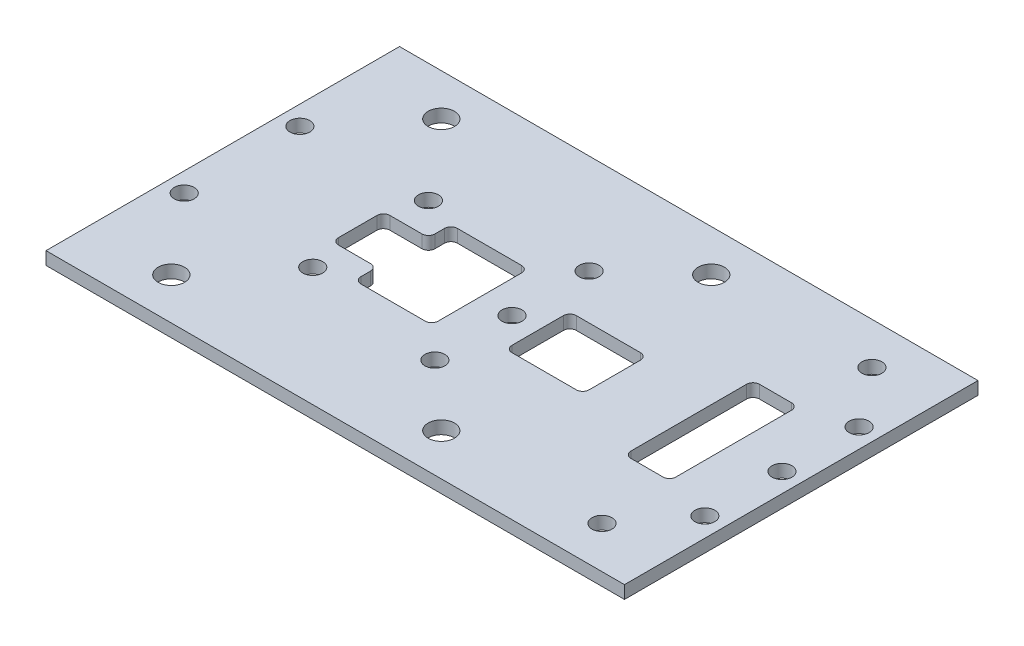
SolidWorks part; units mm, degrees
ref_plane "前视基准面" through (0, 0, 0) normal (0, 0, 1) x (1, 0, 0)
ref_plane "上视基准面" through (0, 0, 0) normal (0, 1, 0) x (1, 0, 0)
ref_plane "右视基准面" through (0, 0, 0) normal (1, 0, 0) x (0, 0, -1)
other "Configuration Table"
sketch "草图1" plane through (0, 0, 0) normal (0, 1, 0) x (1, 0, 0)
  line L1 (45, -27.5) -> (-45, -27.5)
  line L2 (45, -27.5) -> (45, 27.5)
  line L3 (45, 27.5) -> (-45, 27.5)
  line L4 (-45, -27.5) -> (-45, 27.5)
  line L5 (45, -27.5) -> (-45, 27.5) construction
  line L6 (45, 27.5) -> (-45, -27.5) construction
  point P0 (0, 0)
  dimension "D1" = 90
  dimension "D2" = 55
extrude "凸台-拉伸1" add sketch "草图1" along normal blind 2
sketch "草图2" plane through (0, 2, 0) normal (0, 1, 0) x (1, 0, 0)
  line L0 (0, 0) -> (0, 8.8495) construction
  line L1 (0, 0) -> (-20.426, 0) construction
  line L2 (0, 12) -> (0, -12) construction
  line L3 (0, 0) -> (45, 0) construction
  line L4 (-45, 27.5) -> (-45, -27.5) construction
  line L5 (45, -27.5) -> (45, 27.5) construction
  line L6 (42, 0) -> (42, 12) construction
  circle A0 centre (0, -12) radius 1.55
  circle A1 centre (0, 12) radius 1.55
  circle A2 centre (0, 0) radius 1.55
  circle A6 centre (42, 12) radius 1.55
  circle A7 centre (42, 0) radius 1.55
  circle A8 centre (42, -12) radius 1.55
  dimension "D2" = 3.1
  dimension "D4" = 3.1
  dimension "D1" = 24
  dimension "D3" = 45
  dimension "D5" = 24
  dimension "D6" = 3
extrude "切除-拉伸1" cut sketch "草图2" against normal blind 2
sketch "草图3" plane through (0, 2, 0) normal (0, 1, 0) x (1, 0, 0)
  line L0 (35, 27.5) -> (35, -27.5) construction
  line L1 (45, 27.5) -> (-45, 27.5) construction
  line L2 (-45, -27.5) -> (45, -27.5) construction
  line L3 (0, 0) -> (35, 0) construction
  line L4 (45, -27.5) -> (45, 27.5) construction
  circle A0 centre (35, 21) radius 1.55
  circle A1 centre (35, -21) radius 1.55
  dimension "D1" = 3.1
  dimension "D2" = 10
  dimension "D3" = 42
extrude "切除-拉伸2" cut sketch "草图3" against normal blind 10
sketch "草图4" plane through (0, 2, 0) normal (0, 1, 0) x (1, 0, 0)
  line L0 (-32, 27.5) -> (-32, -27.5) construction
  line L1 (45, 27.5) -> (-45, 27.5) construction
  line L2 (-45, -27.5) -> (45, -27.5) construction
  line L3 (-32, 0) -> (0, 0) construction
  line L4 (10, 27.5) -> (10, -27.5) construction
  line L5 (0, 0) -> (10, 0) construction
  circle A0 centre (-32, 21) radius 2.05
  circle A1 centre (-32, -21) radius 2.05
  circle A2 centre (10, 21) radius 2.05
  circle A3 centre (10, -21) radius 2.05
  dimension "D1" = 4.1
  dimension "D2" = 42
  dimension "D3" = 42
  dimension "D4" = 32
  dimension "D5" = 10
extrude "切除-拉伸3" cut sketch "草图4" against normal blind 10
sketch "草图5" plane through (0, 2, 0) normal (0, 1, 0) x (1, 0, 0)
  line L0 (0, 0) -> (-45, 0) construction
  line L1 (-45, 27.5) -> (-45, -27.5) construction
  line L2 (-42, 0) -> (-42, 9) construction
  line L3 (-32, 21) -> (-32, -21) construction
  line L4 (-22, 0) -> (-22, 9) construction
  circle A0 centre (-42, 9) radius 1.55
  circle A1 centre (-42, -9) radius 1.55
  circle A2 centre (-22, -9) radius 1.55
  circle A3 centre (-22, 9) radius 1.55
  dimension "D1" = 3.1
  dimension "D2" = 3
  dimension "D3" = 18
extrude "切除-拉伸4" cut sketch "草图5" against normal blind 10
sketch "草图6" plane through (0, 2, 0) normal (0, 1, 0) x (1, 0, 0)
  line L0 (0, 0) -> (31, 0) construction
  line L2 (34.5, -10) -> (27.5, -10)
  line L3 (34.5, -10) -> (34.5, 10)
  line L4 (34.5, 10) -> (27.5, 10)
  line L5 (27.5, -10) -> (27.5, 10)
  line L6 (34.5, -10) -> (27.5, 10) construction
  line L7 (34.5, 10) -> (27.5, -10) construction
  dimension "D1" = 7
  dimension "D2" = 20
  dimension "D3" = 31
extrude "切除-拉伸5" cut sketch "草图6" against normal blind 10
sketch "草图7" plane through (0, 2, 0) normal (0, 1, 0) x (1, 0, 0)
  line L0 (0, 0) -> (-11, 0) construction
  line L2 (-17, -7.5) -> (-5, -7.5)
  line L3 (-17, -7.5) -> (-17, 7.5)
  line L4 (-17, 7.5) -> (-5, 7.5)
  line L5 (-5, -7.5) -> (-5, 7.5)
  line L6 (-17, -7.5) -> (-5, 7.5) construction
  line L7 (-17, 7.5) -> (-5, -7.5) construction
  dimension "D1" = 15
  dimension "D2" = 12
  dimension "D3" = 11
extrude "切除-拉伸6" cut sketch "草图7" against normal blind 10
sketch "草图8" plane through (0, 2, 0) normal (0, 1, 0) x (1, 0, 0)
  line L0 (0, 0) -> (-29.0782, 0) construction
  line L1 (-17, 4) -> (-24, 4)
  line L2 (-17, 7.5) -> (-17, -7.5) construction
  line L3 (-24, 4) -> (-24, -4)
  line L4 (-24, -4) -> (-17, -4)
  line L5 (-17, -4) -> (-17, 4)
  line L6 (0, 0) -> (20, 0) construction
  line L9 (4, -5) -> (16, -5)
  line L10 (4, -5) -> (4, 5)
  line L11 (4, 5) -> (16, 5)
  line L12 (16, -5) -> (16, 5)
  line L13 (4, -5) -> (16, 5) construction
  line L14 (4, 5) -> (16, -5) construction
  point P7 (10, 0)
  dimension "D1" = 8
  dimension "D2" = 7
  dimension "D3" = 10
  dimension "D4" = 12
  dimension "D5" = 20
extrude "切除-拉伸7" cut sketch "草图8" against normal blind 10
fillet "圆角1" radius 1 16 edges at (34.5, 1, 10) (27.5, 1, 10) (27.5, 1, -10) (34.5, 1, -10) (4, 1, 5) (-5, 1, 7.5) (-17, 1, 7.5) (-17, 1, 4) (-24, 1, -4) (-24, 1, 4) (16, 1, 5) (16, 1, -5) (4, 1, -5) (-5, 1, -7.5) (-17, 1, -7.5) (-17, 1, -4)
